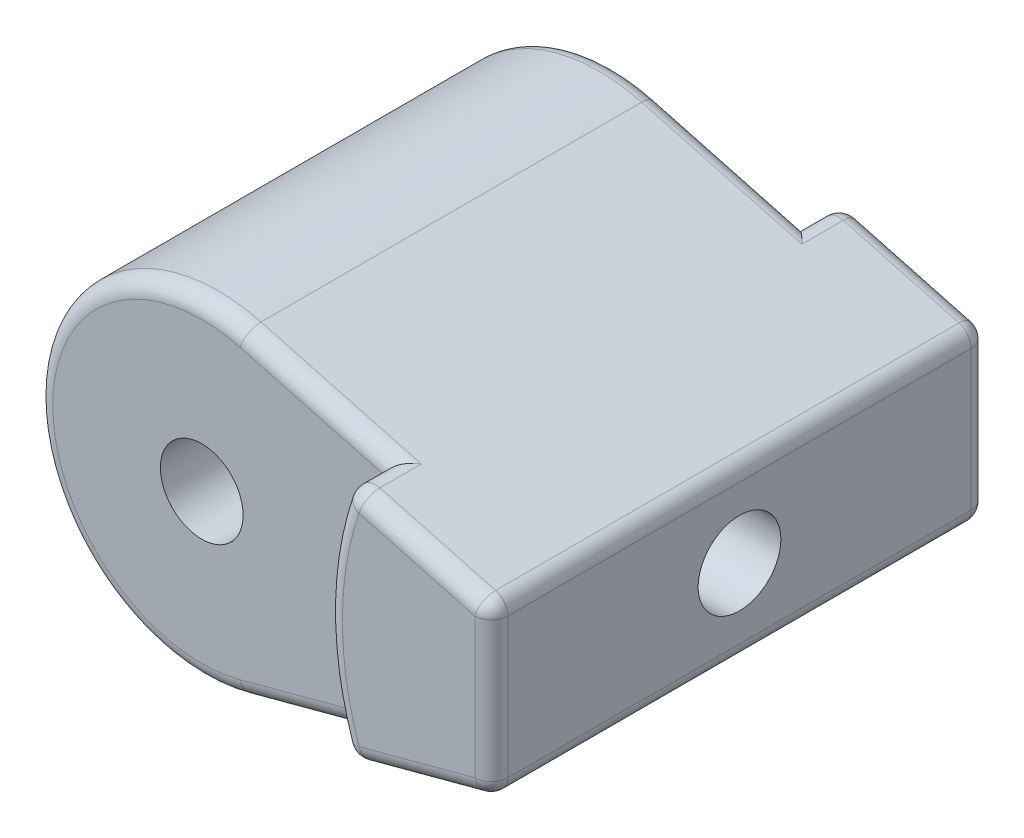
SolidWorks part; units mm, degrees
material "ABS"
ref_plane "Front Plane" through (0, 0, 0) normal (0, 0, 1) x (1, 0, 0)
ref_plane "Top Plane" through (0, 0, 0) normal (0, 1, 0) x (1, 0, 0)
ref_plane "Right Plane" through (0, 0, 0) normal (1, 0, 0) x (0, 0, -1)
sketch "Sketch1" plane through (0, 0, 0) normal (0, 0, 1) x (1, 0, 0)
  line L0 (6.5658, 24.5367) -> (50.8, 12.7)
  line L1 (6.5658, -24.5367) -> (50.8, -12.7)
  line L2 (50.8, 12.7) -> (50.8, -12.7)
  arc A0 (6.5658, 24.5367) -> (6.5658, -24.5367) centre (0, 0) ccw
  circle A1 centre (0, 0) radius 6.35
  point P8 (50.8, 0)
  dimension "D2" = 25.4
  dimension "D4" = 12.7
  dimension "D1" = 50.8
  dimension "D3" = 25.4
extrude "Boss-Extrude1" add sketch "Sketch1" along normal blind 31.75 contours L0 A0 L1 L2 A1
sketch "Sketch2" plane through (0, 0, 31.75) normal (0, 0, 1) x (1, 0, 0)
  line L0 (50.8, 12.7) -> (50.8, -12.7)
  line L1 (50.8, -12.7) -> (6.5658, -24.5367)
  line L2 (50.8, 12.7) -> (6.5658, 24.5367)
  line L3 (25.4, 19.4968) -> (25.4, -19.4968)
  line L4 (6.5658, 24.5367) -> (50.8, 12.7) construction
  circle A0 centre (0, 0) radius 25.4
  arc A1 (6.5658, 24.5367) -> (6.5658, -24.5367) centre (0, 0) ccw construction
  arc A2 (28.9108, 18.5574) -> (28.9108, -18.5574) centre (76.2, 0) ccw
  point P17 (30.4457, 18.1466)
  line M5 (50.8, 12.7) -> (6.5658, 24.5367)
  line M7 (6.5658, -24.5367) -> (50.8, -12.7)
  line M8 (50.8, -12.7) -> (50.8, 12.7)
  dimension "D1" = 50.8
extrude "Boss-Extrude2" add sketch "Sketch2" along normal blind 6.35 contours A0 M7 M8 M5
mirror "Mirror1" about plane through (0, 0, 0) normal (0, 0, 1) of "Boss-Extrude1", "Boss-Extrude2"
sketch "Sketch3" plane through (50.8, 0, 0) normal (1, 0, 0) x (0, 0, -1)
  circle A0 centre (0, 0) radius 6.35
  dimension "D1" = 12.7
extrude "Cut-Extrude1" cut sketch "Sketch3" against normal blind 12.7
fillet "Fillet1" radius 2.54 20 edges at (50.8, 12.7, 0) (50.8, -12.7, 0) (17.7383, 21.547, 31.75) (-25.4, 0, 31.75) (28.9108, 18.5574, 34.925) (28.9108, -18.5574, 34.925) (39.8554, 15.6287, 38.1) (25.4, 0, 38.1) (39.8554, -15.6287, 38.1) (17.7383, -21.547, 31.75) (50.8, 0, 38.1) (17.7383, -21.547, -31.75) (-25.4, 0, -31.75) (17.7383, 21.547, -31.75) (39.8554, 15.6287, -38.1) (28.9108, 18.5574, -34.925) (50.8, 0, -38.1) (39.8554, -15.6287, -38.1) (25.4, 0, -38.1) (28.9108, -18.5574, -34.925)
